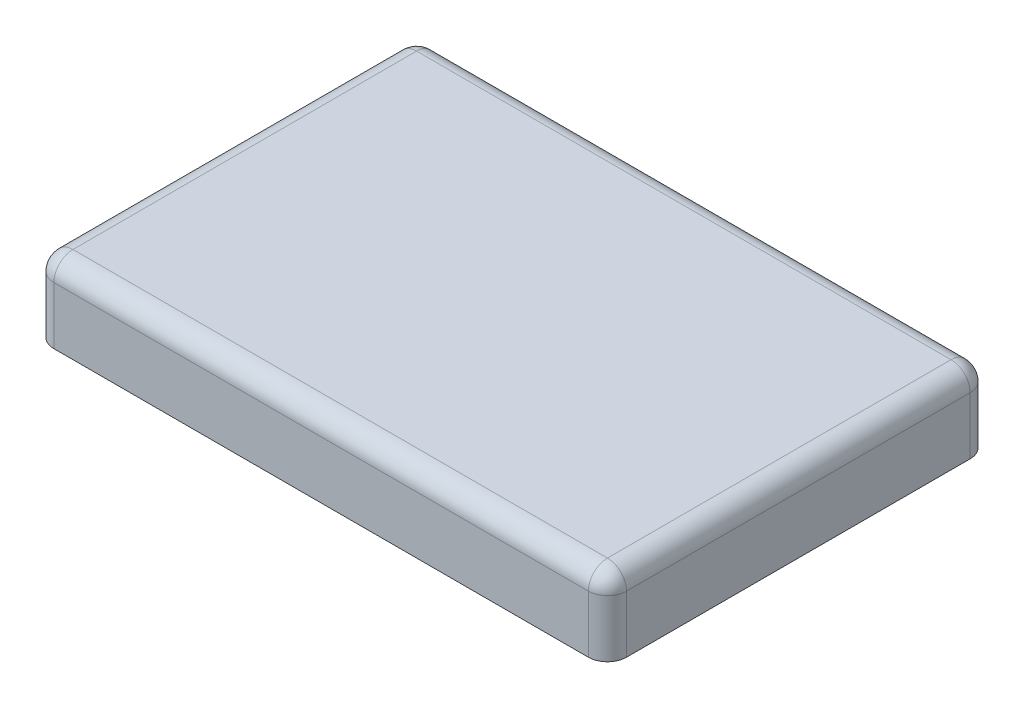
SolidWorks part; units mm, degrees
material "ABS PC"
ref_plane "Front Plane" through (0, 0, 0) normal (0, 0, 1) x (1, 0, 0)
ref_plane "Top Plane" through (0, 0, 0) normal (0, 1, 0) x (1, 0, 0)
ref_plane "Right Plane" through (0, 0, 0) normal (1, 0, 0) x (0, 0, -1)
sketch "Sketch1" plane through (0, 0, 0) normal (0, 1, 0) x (1, 0, 0)
  line L1 (-95.25, -63.5) -> (95.25, -63.5)
  line L2 (-95.25, -63.5) -> (-95.25, 63.5)
  line L3 (-95.25, 63.5) -> (95.25, 63.5)
  line L4 (95.25, -63.5) -> (95.25, 63.5)
  line L5 (-95.25, -63.5) -> (95.25, 63.5) construction
  line L6 (-95.25, 63.5) -> (95.25, -63.5) construction
  point P0 (0, 0)
  dimension "D1" = 127
  dimension "D2" = 190.5
extrude "Boss-Extrude1" add sketch "Sketch1" along normal blind 25.4
fillet "Fillet1" radius 6.35 8 edges at (0, 25.4, 63.5) (-95.25, 25.4, 0) (0, 25.4, -63.5) (95.25, 25.4, 0) (-95.25, 12.7, -63.5) (95.25, 12.7, -63.5) (-95.25, 12.7, 63.5) (95.25, 12.7, 63.5)
shell "Shell1" thickness 2.54
